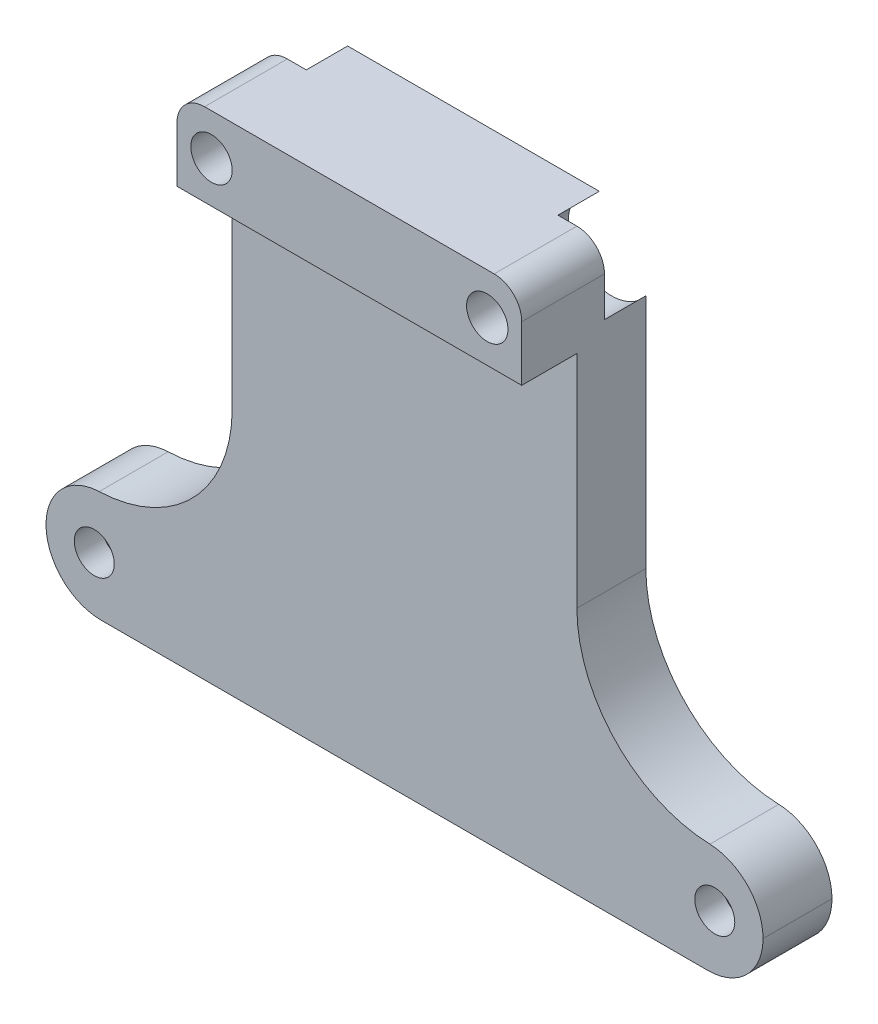
SolidWorks part; units mm, degrees
ref_plane "Спереди" through (0, 0, 0) normal (0, 0, 1) x (1, 0, 0)
ref_plane "Сверху" through (0, 0, 0) normal (0, 1, 0) x (1, 0, 0)
ref_plane "Справа" through (0, 0, 0) normal (1, 0, 0) x (0, 0, -1)
sketch "Эскиз1" plane through (0, 0, 0) normal (0, 0, 1) x (1, 0, 0)
  line L0 (-1000, 0) -> (49000, 0) construction
  line L1 (-26, -4) -> (26, -4)
  line L2 (-26, -4) -> (-26, 4)
  line L3 (-26, 4) -> (26, 4)
  line L4 (26, -4) -> (26, 4)
  line L5 (-26, -4) -> (26, 4) construction
  line L6 (-26, 4) -> (26, -4) construction
  circle A0 centre (-22.5, 0) radius 1.45
  circle A1 centre (22.5, 0) radius 1.45
  point P0 (0, 0)
  dimension "D2" = 2.9
  dimension "D1" = 8
  dimension "D3" = 45
  dimension "D4" = 22.5
  dimension "D5" = 52
extrude "Бобышка-Вытянуть1" add sketch "Эскиз1" along normal blind 5
sketch "Эскиз2" plane through (0, 0, 0) normal (0, 0, -1) x (-1, 0, 0)
  line L0 (-26, 4) -> (26, 4) construction
  line L1 (-12.5, 4) -> (12.5, 4)
  line L2 (-12.5, 4) -> (-12.5, 36)
  line L3 (-12.5, 36) -> (12.5, 36)
  line L4 (12.5, 4) -> (12.5, 36)
  line L5 (-12.5, 4) -> (12.5, 36) construction
  line L6 (-12.5, 36) -> (12.5, 4) construction
  line L7 (-1006.5256, 33) -> (48993.4744, 33) construction
  line L8 (0, -1000) -> (0, 49000) construction
  circle A0 centre (-10, 33) radius 1.5
  circle A1 centre (10, 33) radius 1.5
  point P4 (0, 20)
  dimension "D1" = 20
  dimension "D3" = 3
  dimension "D2" = 10
  dimension "D4" = 25
  dimension "D5" = 3
  dimension "D6" = 32
extrude "Бобышка-Вытянуть2" add sketch "Эскиз2" against normal blind 5
sketch "Эскиз3" plane through (0, 0, 5) normal (0, 0, -1) x (-1, 0, 0)
  line L0 (12.5, 4) -> (12.5, 36) construction
  line L1 (-12.5, 36) -> (12.5, 36)
  line L2 (-12.5, 36) -> (-12.5, 30)
  line L3 (-12.5, 30) -> (12.5, 30)
  line L4 (12.5, 36) -> (12.5, 30)
  line L5 (-12.5, 36) -> (12.5, 30) construction
  line L6 (-12.5, 30) -> (12.5, 36) construction
  circle A0 centre (10, 33) radius 1.5 construction
  circle A1 centre (-10, 33) radius 1.5 construction
  circle A2 centre (10, 33) radius 1.5
  circle A3 centre (-10, 33) radius 1.5
  point P4 (0, 33)
  dimension "D1" = 6
extrude "Бобышка-Вытянуть3" add sketch "Эскиз3" against normal blind 4
fillet "Скругление1" radius 10 2 edges at (12.5, 4, 2.5) (-12.5, 4, 2.5)
fillet "Скругление2" radius 4 4 edges at (-26, -4, 2.5) (-26, 4, 2.5) (26, -4, 2.5) (26, 4, 2.5)
fillet "Скругление3" radius 2 2 edges at (12.5, 36, 4.5) (-12.5, 36, 4.5)
sketch "Эскиз4" plane through (0, 0, 0) normal (0, 0, -1) x (-1, 0, 0)
  circle A0 centre (-10, 33) radius 3.125
  circle A1 centre (10, 33) radius 3.125
  circle A2 centre (-22.5, 0) radius 3.125
  circle A3 centre (22.5, 0) radius 3.125
  dimension "D1" = 6.25
extrude "Вырез-Вытянуть3" cut sketch "Эскиз4" against normal blind 3
